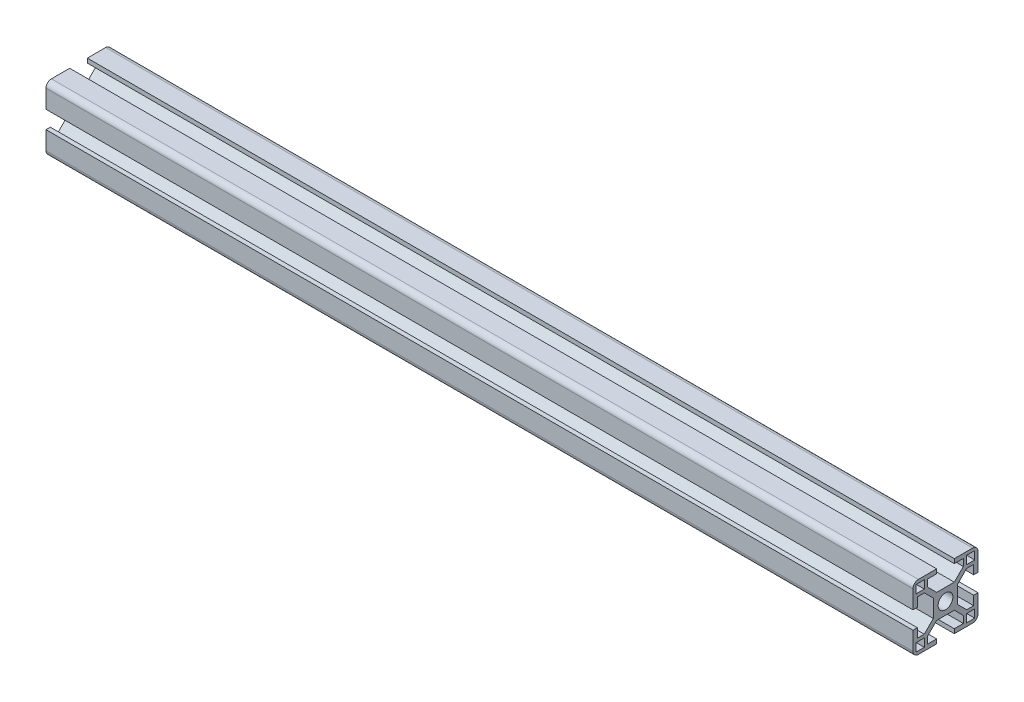
SolidWorks part; units mm, degrees
material "6061 Alloy"
ref_plane "Front Plane" through (0, 0, 0) normal (0, 0, 1) x (1, 0, 0)
ref_plane "Top Plane" through (0, 0, 0) normal (0, 1, 0) x (1, 0, 0)
ref_plane "Right Plane" through (0, 0, 0) normal (1, 0, 0) x (0, 0, -1)
sketch "Sketch1" plane through (0, 0, 0) normal (0, 1, 0) x (1, 0, 0)
  line L0 (0, 0) -> (400, 0)
  dimension "D1" = 400
other "T-slot profiles 3030_2(1)"
ref_plane "Plane1" through (0, 0, 0) normal (1, 0, 0) x (0, 0, -1)
sketch "Sketch17" plane through (0, 0, 0) normal (1, 0, 0) x (0, 0, -1)
  line L0 (0, 15) -> (0, -15) construction
  line L1 (-15, -15) -> (15, -15) construction
  line L2 (-15, -15) -> (-15, 15) construction
  line L3 (-15, 15) -> (15, 15) construction
  line L4 (15, -15) -> (15, 15) construction
  line L5 (-15, -15) -> (15, 15) construction
  line L6 (-15, 15) -> (15, -15) construction
  line L7 (-4.07, 5.6) -> (4.07, 5.6)
  line L8 (0, 0) -> (15, 0) construction
  line L9 (-4.07, -5.6) -> (4.07, -5.6)
  line L10 (5.6, -4.07) -> (5.6, 4.07)
  line L11 (-5.6, -4.07) -> (-5.6, 4.07)
  line L12 (-4.07, 5.6) -> (-8.25, 9.78)
  line L13 (4.07, 5.6) -> (8.25, 9.78)
  line L14 (-8.25, 9.78) -> (8.25, 9.78) construction
  line L15 (8.25, 9.78) -> (8.25, 13)
  line L16 (8.25, 13) -> (4.07, 13)
  line L17 (4.07, 13) -> (4.07, 15)
  line L18 (4.07, 15) -> (12.5, 15)
  line L19 (15, 12.5) -> (15, 4.07)
  line L20 (9.78, 8.25) -> (13, 8.25)
  line L21 (13, 8.25) -> (13, 4.07)
  line L22 (9.78, 8.25) -> (5.6, 4.07)
  line L23 (8.25, 9.78) -> (9.78, 8.25) construction
  line L24 (13, 4.07) -> (15, 4.07)
  line L25 (5.6, -4.07) -> (9.78, -8.25)
  line L26 (9.75, 13.5) -> (13.5, 13.5)
  line L27 (9.75, 13.5) -> (9.75, 9.75)
  line L28 (9.75, 9.75) -> (13.5, 9.75)
  line L29 (13.5, 13.5) -> (13.5, 9.75)
  line L30 (9.75, 13.5) -> (13.5, 9.75) construction
  line L31 (9.75, 9.75) -> (13.5, 13.5) construction
  line L32 (9.78, -8.25) -> (13, -8.25)
  line L33 (13, -8.25) -> (13, -4.07)
  line L34 (13, -4.07) -> (15, -4.07)
  line L35 (15, -4.07) -> (15, -12.5)
  line L36 (4.07, -5.6) -> (8.25, -9.78)
  line L37 (8.25, -9.78) -> (8.25, -13)
  line L38 (8.25, -13) -> (4.07, -13)
  line L39 (4.07, -13) -> (4.07, -15)
  line L40 (4.07, -15) -> (12.5, -15)
  line L41 (-4.07, -5.6) -> (-8.25, -9.78)
  line L42 (-8.25, -9.78) -> (-8.25, -13)
  line L43 (-8.25, -13) -> (-4.07, -13)
  line L44 (-4.07, -13) -> (-4.07, -15)
  line L45 (-4.07, -15) -> (-12.5, -15)
  line L46 (-8.25, 9.78) -> (-8.25, 13)
  line L47 (-8.25, 13) -> (-4.07, 13)
  line L48 (-4.07, 13) -> (-4.07, 15)
  line L49 (-4.07, 15) -> (-12.5, 15)
  line L50 (-5.6, 4.07) -> (-9.78, 8.25)
  line L51 (-9.78, 8.25) -> (-13, 8.25)
  line L52 (-13, 8.25) -> (-13, 4.07)
  line L53 (-13, 4.07) -> (-15, 4.07)
  line L54 (-15, 4.07) -> (-15, 12.5)
  line L55 (-5.6, -4.07) -> (-9.78, -8.25)
  line L56 (-9.78, -8.25) -> (-13, -8.25)
  line L57 (-13, -8.25) -> (-13, -4.07)
  line L58 (-13, -4.07) -> (-15, -4.07)
  line L59 (-15, -4.07) -> (-15, -12.5)
  line L60 (9.75, -9.75) -> (13.5, -9.75)
  line L61 (13.5, -13.5) -> (13.5, -9.75)
  line L62 (9.75, -13.5) -> (13.5, -13.5)
  line L63 (9.75, -13.5) -> (9.75, -9.75)
  line L64 (-9.75, 9.75) -> (-13.5, 9.75)
  line L65 (-13.5, 13.5) -> (-13.5, 9.75)
  line L66 (-9.75, 13.5) -> (-13.5, 13.5)
  line L67 (-9.75, 13.5) -> (-9.75, 9.75)
  line L68 (-9.75, -13.5) -> (-9.75, -9.75)
  line L69 (-9.75, -13.5) -> (-13.5, -13.5)
  line L70 (-13.5, -13.5) -> (-13.5, -9.75)
  line L71 (-9.75, -9.75) -> (-13.5, -9.75)
  arc A0 (-15, 12.5) -> (-12.5, 15) centre (-12.5, 12.5) cw
  arc A1 (12.5, -15) -> (15, -12.5) centre (12.5, -12.5) ccw
  arc A2 (15, 12.5) -> (12.5, 15) centre (12.5, 12.5) ccw
  arc A3 (-12.5, -15) -> (-15, -12.5) centre (-12.5, -12.5) cw
  circle A4 centre (0, 0) radius 3.4
  point P0 (0, 0)
  point P6 (0, 0)
  point P7 (-12.5, 12.5)
  point P26 (0, 5.6)
  point P32 (5.6, 0)
  point P44 (11.625, 11.625)
  dimension "D4" = 6.8
  dimension "D3" = 2.5
  dimension "D1" = 30
  dimension "D2" = 30
  dimension "D5" = 8.14
  dimension "D6" = 9.4
  dimension "D7" = 8.14
  dimension "D8" = 9.4
  dimension "D9" = 16.5
  dimension "D10" = 2
  dimension "D11" = 2
  dimension "D12" = 3.75
  dimension "D13" = 3.75
  dimension "D14" = 1.5
  dimension "D15" = 2
  dimension "D16" = 2
  dimension "D17" = 2
  dimension "D18" = 2
  dimension "D19" = 2
  dimension "D20" = 2
